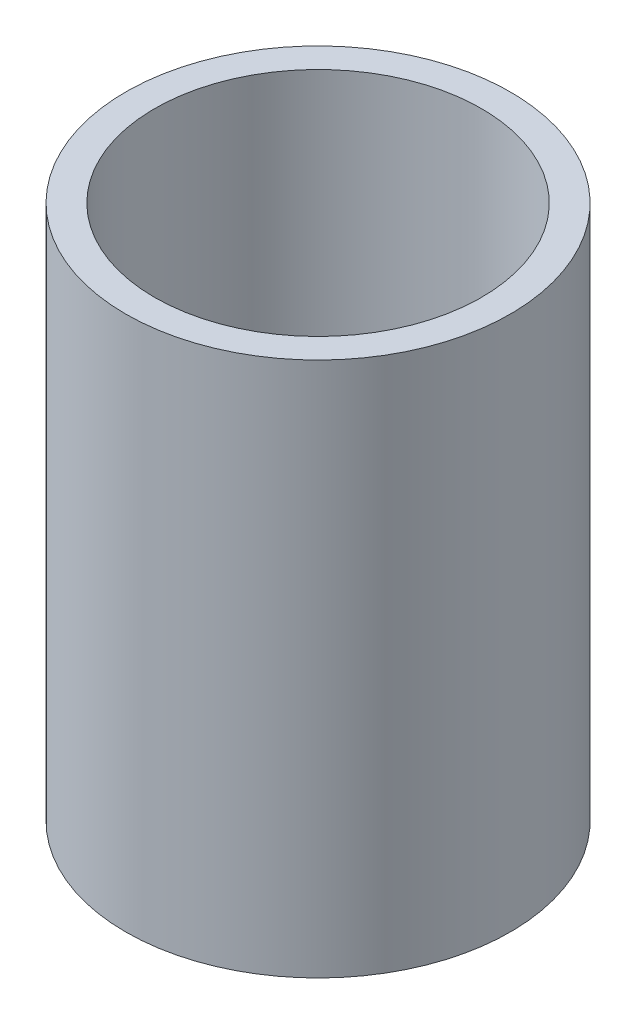
SolidWorks part; units mm, degrees
material "PVC 경질"
ref_plane "정면" through (0, 0, 0) normal (0, 0, 1) x (1, 0, 0)
ref_plane "윗면" through (0, 0, 0) normal (0, 1, 0) x (1, 0, 0)
ref_plane "우측면" through (0, 0, 0) normal (1, 0, 0) x (0, 0, -1)
other "질량 중심(COM)"
sketch "스케치1" plane through (0, 0, 0) normal (0, 1, 0) x (1, 0, 0)
  circle A0 centre (0, 0) radius 30
  dimension "D1" = 60
extrude "보스-돌출1" add sketch "스케치1" against normal blind 83.46 contours A0
sketch "스케치2" plane through (0, 0, 0) normal (0, 1, 0) x (1, 0, 0)
  circle A0 centre (0, 0) radius 25.5
  dimension "D1" = 51
extrude "컷-돌출1" cut sketch "스케치2" against normal blind 83.46 contours A0
